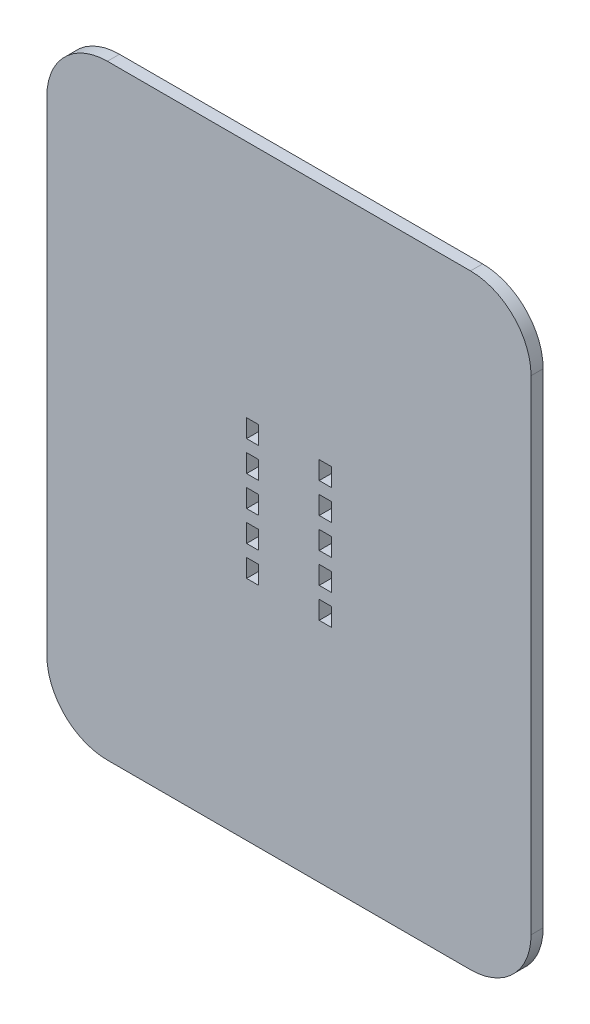
SolidWorks part; units mm, degrees
ref_plane "Front Plane" through (0, 0, 0) normal (0, 0, 1) x (1, 0, 0)
ref_plane "Top Plane" through (0, 0, 0) normal (0, 1, 0) x (1, 0, 0)
ref_plane "Right Plane" through (0, 0, 0) normal (1, 0, 0) x (0, 0, -1)
sketch "Sketch1" plane through (0, 0, 0) normal (0, 0, 1) x (1, 0, 0)
  line L1 (-80, -100) -> (80, -100)
  line L2 (-80, -100) -> (-80, 100)
  line L3 (-80, 100) -> (80, 100)
  line L4 (80, -100) -> (80, 100)
  line L5 (-80, -100) -> (80, 100) construction
  line L6 (-80, 100) -> (80, -100) construction
  point P0 (0, 0)
  dimension "D1" = 160
  dimension "D2" = 200
extrude "Boss-Extrude1" add sketch "Sketch1" along normal blind 4
sketch "Sketch2" plane through (0, 0, 4) normal (0, 0, 1) x (1, 0, 0)
  line L1 (10, 21) -> (14, 21)
  line L2 (10, 21) -> (10, 15)
  line L3 (10, 15) -> (14, 15)
  line L4 (14, 21) -> (14, 15)
  line L5 (10, 11) -> (14, 11)
  line L6 (10, 11) -> (10, 5)
  line L7 (10, 5) -> (14, 5)
  line L8 (14, 11) -> (14, 5)
  line L9 (10, 1) -> (14, 1)
  line L10 (10, 1) -> (10, -5)
  line L11 (10, -5) -> (14, -5)
  line L12 (14, 1) -> (14, -5)
  line L13 (10, -9) -> (14, -9)
  line L14 (10, -9) -> (10, -15)
  line L15 (10, -15) -> (14, -15)
  line L16 (14, -9) -> (14, -15)
  line L17 (10, -19) -> (14, -19)
  line L18 (10, -19) -> (10, -25)
  line L19 (10, -25) -> (14, -25)
  line L20 (14, -19) -> (14, -25)
  dimension "D1" = 10
  dimension "D2" = 21
  dimension "D3" = 6
  dimension "D4" = 4
  dimension "D5" = 4
  dimension "D6" = 6
  dimension "D7" = 4
  dimension "D8" = 0
  dimension "D9" = 6
  dimension "D10" = 6
  dimension "D11" = 4
  dimension "D12" = 4
  dimension "D13" = 0
  dimension "D14" = 4
  dimension "D15" = 4
  dimension "D16" = 0
  dimension "D17" = 6
  dimension "D18" = 4
  dimension "D19" = 0
  dimension "D20" = 4
extrude "Cut-Extrude1" cut sketch "Sketch2" against normal blind 4
mirror "Mirror1" about plane through (0, 0, 0) normal (1, 0, 0) of "Cut-Extrude1"
fillet "Fillet1" radius 20 4 edges at (-80, -100, 2) (80, -100, 2) (-80, 100, 2) (80, 100, 2)
